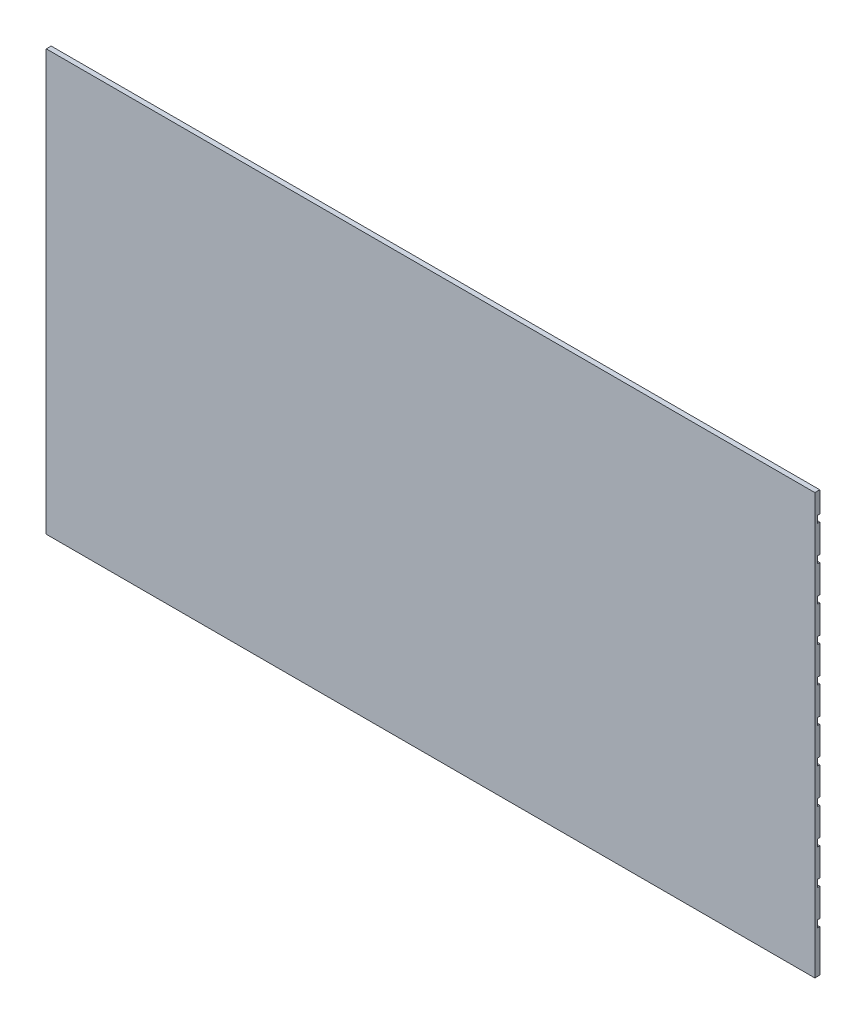
SolidWorks part; units mm, degrees
ref_plane "Front Plane" through (0, 0, 0) normal (0, 0, 1) x (1, 0, 0)
ref_plane "Top Plane" through (0, 0, 0) normal (0, 1, 0) x (1, 0, 0)
ref_plane "Right Plane" through (0, 0, 0) normal (1, 0, 0) x (0, 0, -1)
sketch "Sketch2" plane through (0, 0, 0) normal (1, 0, 0) x (0, 0, -1)
  line L1 (0, 0) -> (17.78, 0)
  line L2 (0, 0) -> (0, -1524)
  line L3 (0, -1524) -> (17.78, -1524)
  line L4 (17.78, 0) -> (17.78, -1524)
  dimension "D1" = 17.78
  dimension "D2" = 1524
extrude "Boss-Extrude1" add sketch "Sketch2" along normal blind 2786.38
sketch "Sketch3" plane through (0, 0, -17.78) normal (0, 0, -1) x (-1, 0, 0)
  line L0 (-2786.38, -1524) -> (-2786.38, 0) construction
  line L1 (-2786.38, -76.2) -> (0, -76.2)
  line L2 (-2786.38, -76.2) -> (-2786.38, -101.6)
  line L3 (-2786.38, -101.6) -> (0, -101.6)
  line L4 (0, -76.2) -> (0, -101.6)
  line L5 (0, -1524) -> (0, 0) construction
  line L6 (-2786.38, 0) -> (0, 0) construction
  line L7 (-2786.38, -228.6) -> (0, -228.6)
  line L8 (-2786.38, -203.2) -> (0, -203.2)
  line L9 (-2786.38, -203.2) -> (-2786.38, -228.6)
  line L10 (0, -203.2) -> (0, -228.6)
  line L11 (-2786.38, -355.6) -> (0, -355.6)
  line L12 (-2786.38, -330.2) -> (0, -330.2)
  line L13 (-2786.38, -330.2) -> (-2786.38, -355.6)
  line L14 (0, -330.2) -> (0, -355.6)
  line L15 (-2786.38, -482.6) -> (0, -482.6)
  line L16 (-2786.38, -457.2) -> (0, -457.2)
  line L17 (-2786.38, -457.2) -> (-2786.38, -482.6)
  line L18 (0, -457.2) -> (0, -482.6)
  line L19 (-2786.38, -609.6) -> (0, -609.6)
  line L20 (-2786.38, -584.2) -> (0, -584.2)
  line L21 (-2786.38, -584.2) -> (-2786.38, -609.6)
  line L22 (0, -584.2) -> (0, -609.6)
  line L23 (-2786.38, -736.6) -> (0, -736.6)
  line L24 (-2786.38, -711.2) -> (0, -711.2)
  line L25 (-2786.38, -711.2) -> (-2786.38, -736.6)
  line L26 (0, -711.2) -> (0, -736.6)
  line L27 (-2786.38, -863.6) -> (0, -863.6)
  line L28 (-2786.38, -838.2) -> (0, -838.2)
  line L29 (-2786.38, -838.2) -> (-2786.38, -863.6)
  line L30 (0, -838.2) -> (0, -863.6)
  line L31 (-2786.38, -990.6) -> (0, -990.6)
  line L32 (-2786.38, -965.2) -> (0, -965.2)
  line L33 (-2786.38, -965.2) -> (-2786.38, -990.6)
  line L34 (0, -965.2) -> (0, -990.6)
  line L35 (-2786.38, -1117.6) -> (0, -1117.6)
  line L36 (-2786.38, -1092.2) -> (0, -1092.2)
  line L37 (-2786.38, -1092.2) -> (-2786.38, -1117.6)
  line L38 (0, -1092.2) -> (0, -1117.6)
  line L39 (-2786.38, -1244.6) -> (0, -1244.6)
  line L40 (-2786.38, -1219.2) -> (0, -1219.2)
  line L41 (-2786.38, -1219.2) -> (-2786.38, -1244.6)
  line L42 (0, -1219.2) -> (0, -1244.6)
  line L43 (-2786.38, -1371.6) -> (0, -1371.6)
  line L44 (-2786.38, -1346.2) -> (0, -1346.2)
  line L45 (-2786.38, -1346.2) -> (-2786.38, -1371.6)
  line L46 (0, -1346.2) -> (0, -1371.6)
  dimension "D1" = 25.4
  dimension "D2" = 76.2
  dimension "D3" = 11
extrude "Cut-Extrude1" cut sketch "Sketch3" against normal blind 7.62
